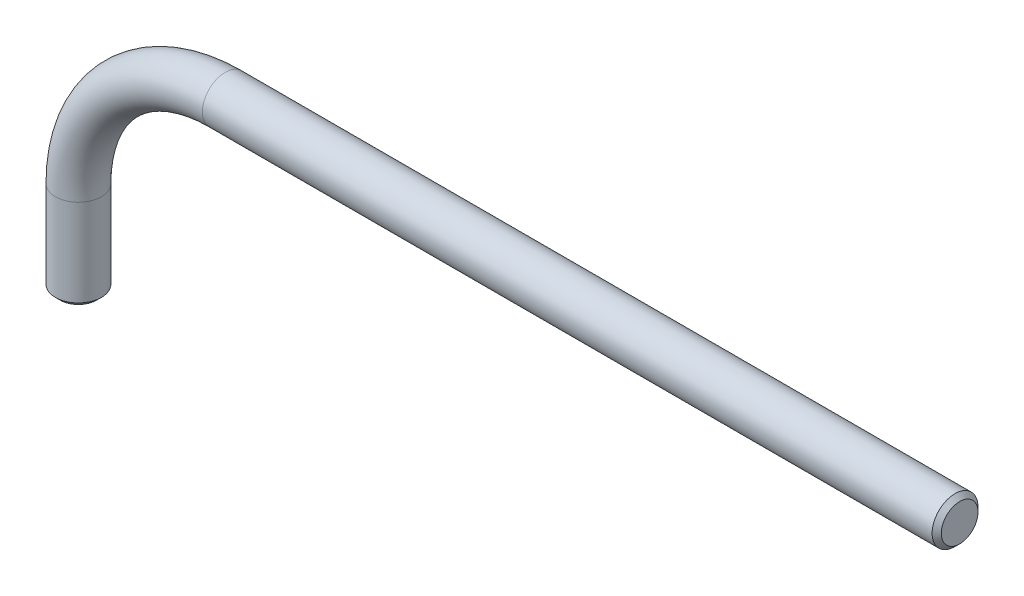
SolidWorks part; units mm, degrees
ref_plane "Front Plane" through (0, 0, 0) normal (0, 0, 1) x (1, 0, 0)
ref_plane "Top Plane" through (0, 0, 0) normal (0, 1, 0) x (1, 0, 0)
ref_plane "Right Plane" through (0, 0, 0) normal (1, 0, 0) x (0, 0, -1)
sketch "Sketch1" plane through (0, 0, 0) normal (0, 1, 0) x (1, 0, 0)
  circle A0 centre (0, 0) radius 2.5
  dimension "D1" = 5
sketch "Sketch2" plane through (0, 0, 0) normal (0, 0, 1) x (1, 0, 0)
  line L0 (0, 0) -> (0, 10)
  line L1 (16, 26) -> (96, 26)
  arc A0 (0, 10) -> (16, 26) centre (16, 10) cw
  point P5 (0, 0)
  point P7 (0, 14.5071)
  dimension "D1" = 16
  dimension "D2" = 26
  dimension "D3" = 96
sweep "Sweep1" add profiles "Sketch1" path "Sketch2"
chamfer "Chamfer1" distance 0.5 angle 45 2 edges at (96, 26, 2.5) (0, 0, 2.5)
